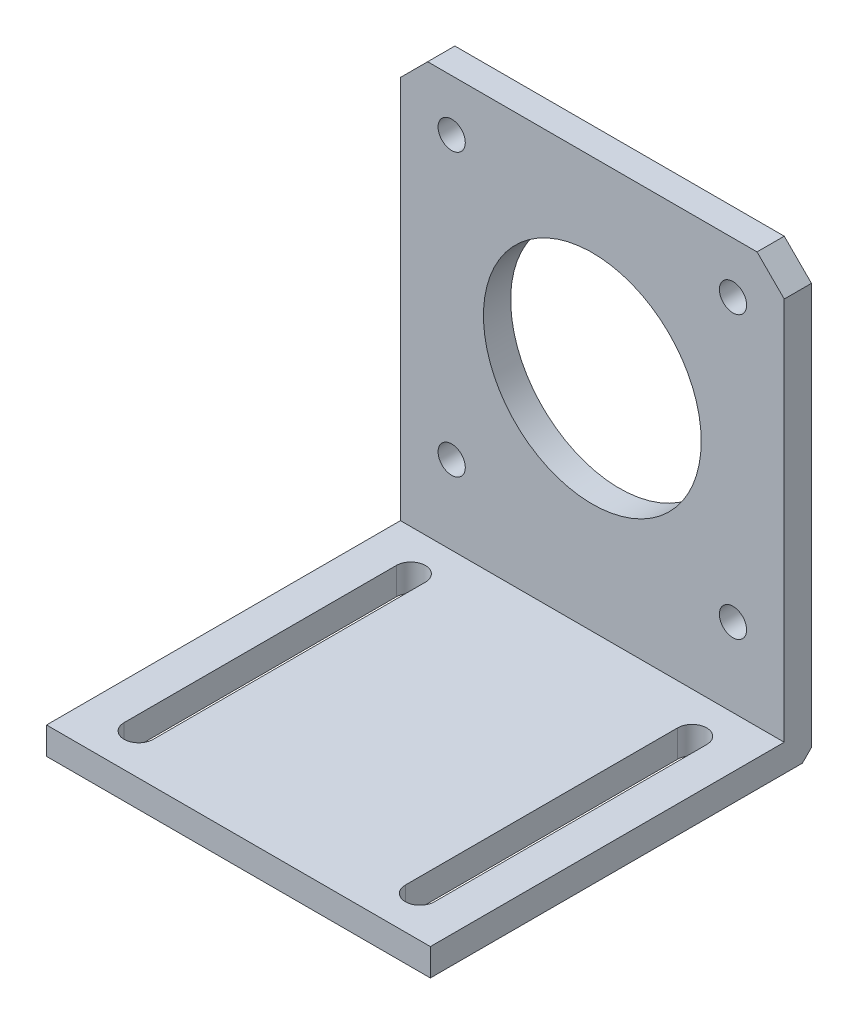
SolidWorks part; units mm, degrees
ref_plane "Front Plane" through (0, 0, 0) normal (0, 0, 1) x (1, 0, 0)
ref_plane "Top Plane" through (0, 0, 0) normal (0, 1, 0) x (1, 0, 0)
ref_plane "Right Plane" through (0, 0, 0) normal (1, 0, 0) x (0, 0, -1)
sketch "Sketch1" plane through (0, 0, 0) normal (0, 0, 1) x (1, 0, 0)
  line L0 (-21.15, 18.15) -> (-18.15, 21.15)
  line L1 (-18.15, 21.15) -> (18.15, 21.15)
  line L2 (-21.15, 18.15) -> (-21.15, -18.15)
  line L3 (-18.15, -21.15) -> (18.15, -21.15)
  line L4 (21.15, 18.15) -> (21.15, -18.15)
  line L5 (-21.15, 21.15) -> (21.15, -21.15) construction
  line L6 (-21.15, -21.15) -> (21.15, 21.15) construction
  line L7 (-21.15, -18.15) -> (-18.15, -21.15)
  line L8 (18.15, -21.15) -> (21.15, -18.15)
  line L9 (18.15, 21.15) -> (21.15, 18.15)
  circle A0 centre (-15.5, 15.5) radius 1.5
  circle A1 centre (15.5, 15.5) radius 1.5
  circle A2 centre (15.5, -15.5) radius 1.5
  circle A3 centre (-15.5, -15.5) radius 1.5
  circle A4 centre (0, 0) radius 12
  point P0 (0, 0)
  point P25 (0, 0)
  dimension "D4" = 3
  dimension "D10" = 24
  dimension "D1" = 42.3
  dimension "D2" = 42.3
  dimension "D3" = 15.5
  dimension "D9" = 4
extrude "Boss-Extrude1" add sketch "Sketch1" along normal blind 3
sketch "Sketch2" plane through (0, 0, 0) normal (0, 0, -1) x (-1, 0, 0)
  line L0 (21.15, -18.15) -> (18.15, -21.15) construction
  line L1 (-18.15, -21.15) -> (-21.15, -18.15) construction
  line L2 (21.15, -18.15) -> (18.15, -21.15)
  line L3 (-18.15, -21.15) -> (-21.15, -18.15)
  line L4 (-21.15, -18.15) -> (-21.15, -27.15)
  line L5 (-21.15, -27.15) -> (21.15, -27.15)
  line L6 (21.15, -27.15) -> (21.15, -18.15)
  line L7 (18.15, -21.15) -> (-18.15, -21.15) construction
  line L8 (-18.15, -21.15) -> (18.15, -21.15)
  dimension "D1" = 6
extrude "Boss-Extrude2" add sketch "Sketch2" against normal blind 3
sketch "Sketch3" plane through (0, 0, 3) normal (0, 0, 1) x (1, 0, 0)
  line L0 (21.15, -27.15) -> (21.15, 18.15) construction
  line L1 (-21.15, -27.15) -> (21.15, -27.15)
  line L2 (-21.15, -27.15) -> (-21.15, -24.15)
  line L3 (-21.15, -24.15) -> (21.15, -24.15)
  line L4 (21.15, -27.15) -> (21.15, -24.15)
  dimension "D1" = 3
extrude "Boss-Extrude3" add sketch "Sketch3" along normal blind 39
chamfer "Chamfer1" distance 1 angle 45 1 edges at (0, -27.15, 0)
sketch "Sketch4" plane through (0, -24.15, 0) normal (0, 1, 0) x (1, 0, 0)
  line L0 (15.5, -7.5) -> (15.5, -37.5) construction
  line L1 (17.1, -7.5) -> (17.1, -37.5)
  line L2 (13.9, -7.5) -> (13.9, -37.5)
  line L3 (0, -3) -> (0, -42) construction
  line L4 (18.15, -3) -> (-18.15, -3) construction
  line L5 (21.15, -42) -> (-21.15, -42) construction
  line L6 (-15.5, -7.5) -> (-15.5, -37.5) construction
  line L7 (-17.1, -7.5) -> (-17.1, -37.5)
  line L8 (-13.9, -7.5) -> (-13.9, -37.5)
  arc A0 (17.1, -7.5) -> (13.9, -7.5) centre (15.5, -7.5) ccw
  arc A1 (13.9, -37.5) -> (17.1, -37.5) centre (15.5, -37.5) ccw
  arc A2 (-17.1, -7.5) -> (-13.9, -7.5) centre (-15.5, -7.5) cw
  arc A3 (-13.9, -37.5) -> (-17.1, -37.5) centre (-15.5, -37.5) cw
  point P2 (15.5, -22.5)
  point P16 (-15.5, -22.5)
  dimension "D1" = 1.6
  dimension "D2" = 15.5
  dimension "D3" = 30
  dimension "D4" = 19.5
extrude "Cut-Extrude1" cut sketch "Sketch4" against normal blind 3
